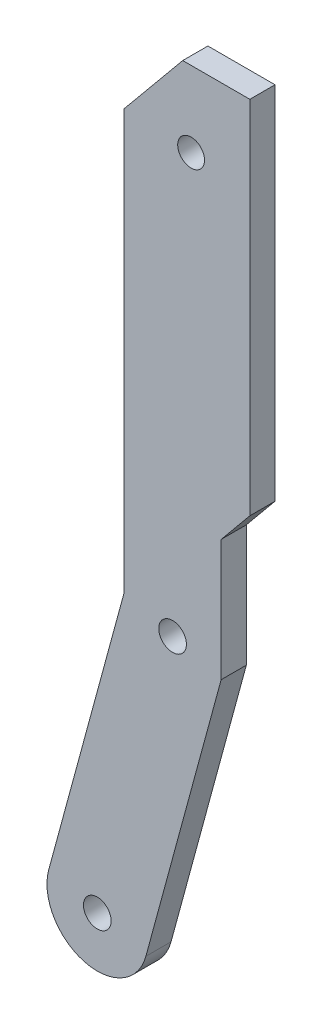
SolidWorks part; units mm, degrees
ref_plane "Front Plane" through (0, 0, 0) normal (0, 0, 1) x (1, 0, 0)
ref_plane "Top Plane" through (0, 0, 0) normal (0, 1, 0) x (1, 0, 0)
ref_plane "Right Plane" through (0, 0, 0) normal (1, 0, 0) x (0, 0, -1)
sketch "Sketch1" plane through (0, 0, 0) normal (0, 0, 1) x (1, 0, 0)
  line L0 (-37.4134, 4.9713) -> (-28.4406, 38.0127) construction
  line L1 (-43.2037, 6.5438) -> (-34.2309, 39.5851)
  line L2 (-31.6231, 3.3989) -> (-22.6503, 36.4403)
  line L3 (-34.2309, 39.5851) -> (-34.2309, 89.5851)
  line L4 (-34.2309, 89.5851) -> (-27.2309, 98.0704)
  line L5 (-27.2309, 98.0704) -> (-19.2309, 98.0704)
  line L6 (-19.2309, 98.0704) -> (-19.2309, 55.0705)
  line L7 (-19.2309, 55.0705) -> (-22.6503, 50.9256)
  line L8 (-22.6503, 50.9256) -> (-22.6503, 36.4403)
  arc A0 (-43.2037, 6.5438) -> (-31.6231, 3.3989) centre (-37.4134, 4.9713) ccw
  arc A1 (-22.6503, 36.4403) -> (-34.2309, 39.5851) centre (-28.4406, 38.0127) ccw
  circle A2 centre (-28.4406, 38.0127) radius 1.65
  circle A3 centre (-37.4134, 4.9713) radius 1.65
  circle A4 centre (-26.2309, 89.0704) radius 1.6
  point P4 (-32.927, 21.492)
  dimension "D1" = 12
  dimension "D7" = 3.3
  dimension "D8" = 3.3
  dimension "D9" = 3.2
  dimension "D2" = 42.9999
  dimension "D3" = 8
  dimension "D4" = 50
  dimension "D5" = 15
  dimension "D6" = 11
  dimension "D10" = 9
  dimension "D11" = 7
extrude "Boss-Extrude1" add sketch "Sketch1" along normal blind 3
